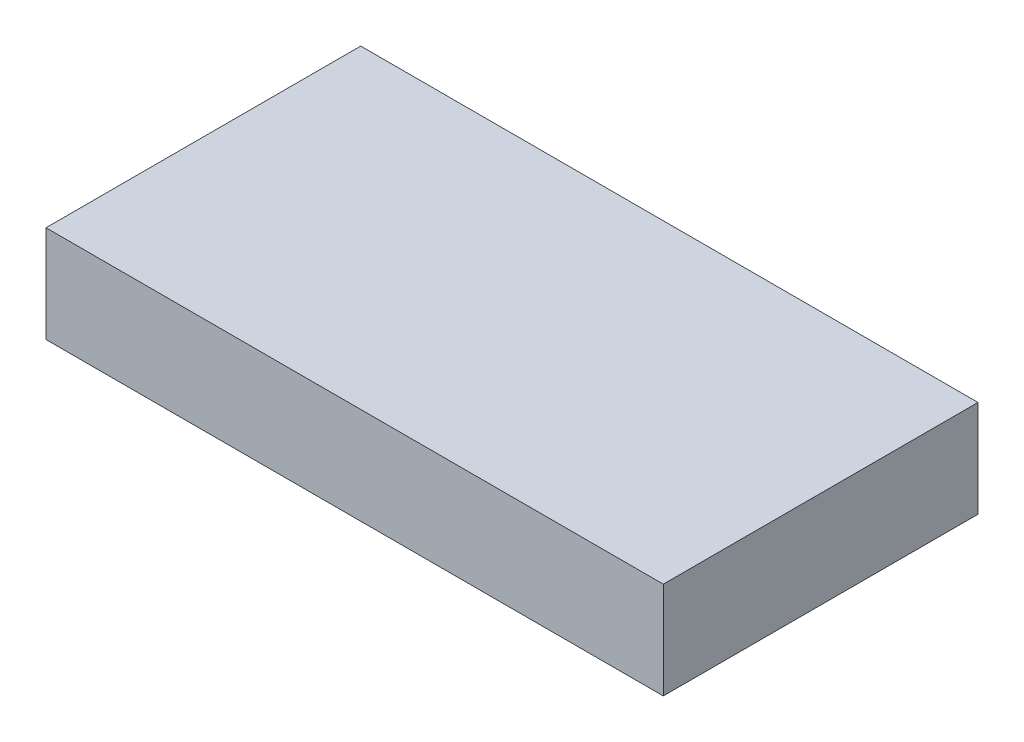
SolidWorks part; units mm, degrees
ref_plane "前视基准面" through (0, 0, 0) normal (0, 0, 1) x (1, 0, 0)
ref_plane "上视基准面" through (0, 0, 0) normal (0, 1, 0) x (1, 0, 0)
ref_plane "右视基准面" through (0, 0, 0) normal (1, 0, 0) x (0, 0, -1)
sketch "草图1" plane through (0, 0, 0) normal (0, 1, 0) x (1, 0, 0)
  line L1 (0, 0) -> (51, 0)
  line L2 (0, 0) -> (0, -26)
  line L3 (0, -26) -> (51, -26)
  line L4 (51, 0) -> (51, -26)
  dimension "D1" = 51
  dimension "D2" = 26
extrude "凸台-拉伸1" add sketch "草图1" along normal blind 8
